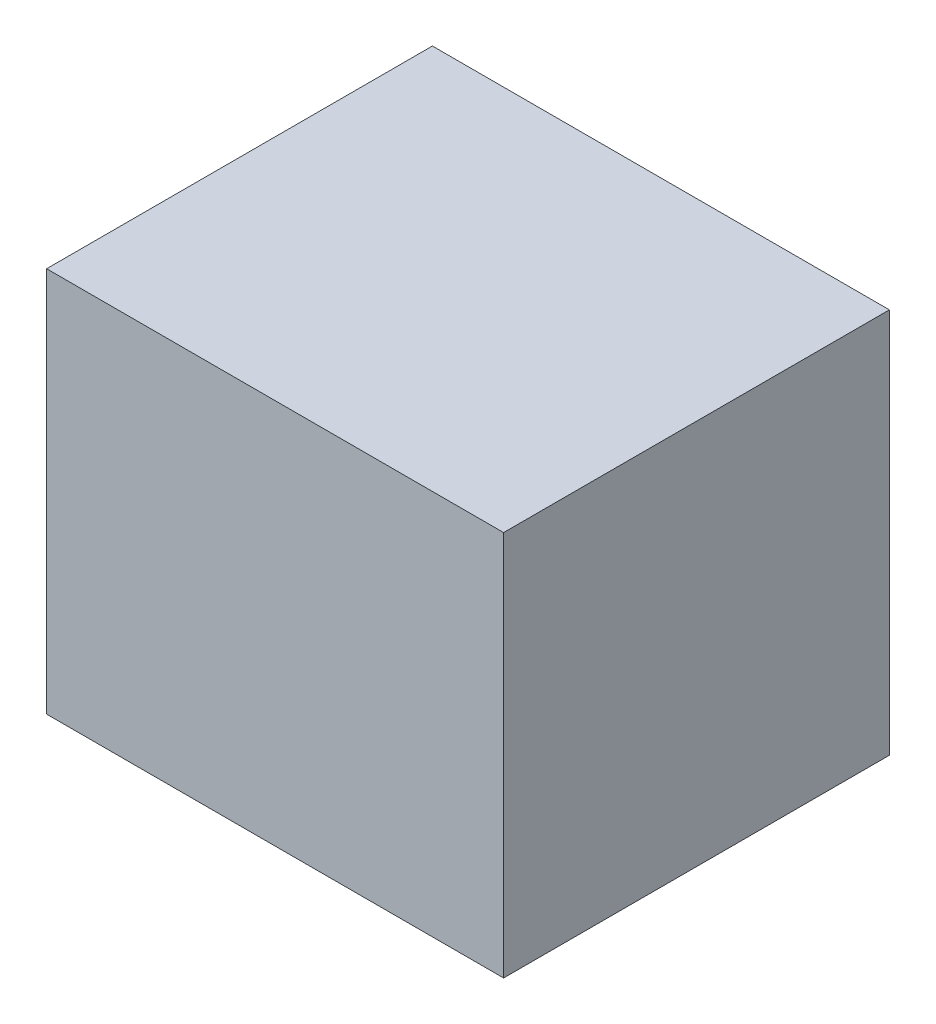
SolidWorks part; units mm, degrees
ref_plane "Front Plane" through (0, 0, 0) normal (0, 0, 1) x (1, 0, 0)
ref_plane "Top Plane" through (0, 0, 0) normal (0, 1, 0) x (1, 0, 0)
ref_plane "Right Plane" through (0, 0, 0) normal (1, 0, 0) x (0, 0, -1)
sketch "Sketch1" plane through (0, 0, 0) normal (0, 0, 1) x (1, 0, 0)
  line L1 (-122.2375, -103.1875) -> (122.2375, -103.1875)
  line L2 (-122.2375, -103.1875) -> (-122.2375, 103.1875)
  line L3 (-122.2375, 103.1875) -> (122.2375, 103.1875)
  line L4 (122.2375, -103.1875) -> (122.2375, 103.1875)
  line L5 (-122.2375, -103.1875) -> (122.2375, 103.1875) construction
  line L6 (-122.2375, 103.1875) -> (122.2375, -103.1875) construction
  point P0 (0, 0)
  dimension "D1" = 244.475
  dimension "D2" = 206.375
extrude "Boss-Extrude1" add sketch "Sketch1" against normal blind 206.375 contours L3 L4 L1 L2
shell "Shell1" thickness 3.175
sketch "Sketch2" plane through (0, 0, 0) normal (0, 0, 1) x (1, 0, 0)
  line L0 (-122.2375, -103.1875) -> (122.2375, -103.1875) construction
  line L1 (-66.3003, -100.1775) -> (51.5557, -100.1775)
  line L2 (-66.3003, -100.1775) -> (-66.3003, -59.2835)
  line L3 (-66.3003, -59.2835) -> (51.5557, -59.2835)
  line L4 (51.5557, -100.1775) -> (51.5557, -59.2835)
  line L5 (-119.0625, 68.2625) -> (-68.7705, 68.2625)
  line L6 (-119.0625, 68.2625) -> (-119.0625, -100.0125)
  line L7 (-119.0625, -100.0125) -> (-68.7705, -100.0125)
  line L8 (-68.7705, 68.2625) -> (-68.7705, -100.0125)
  line L9 (-122.2375, -103.1875) -> (-122.2375, 103.1875) construction
  line L10 (-66.3003, -46.8375) -> (51.5557, -46.8375)
  line L11 (55.093, -100.485) -> (95.987, -100.485)
  line L12 (55.093, -100.485) -> (55.093, 17.371)
  line L13 (55.093, 17.371) -> (95.987, 17.371)
  line L14 (95.987, -100.485) -> (95.987, 17.371)
  line L15 (99.3741, 18.9815) -> (124.7741, 18.9815)
  line L16 (99.3741, 18.9815) -> (99.3741, -100.3985)
  line L17 (99.3741, -100.3985) -> (124.7741, -100.3985)
  line L18 (124.7741, 18.9815) -> (124.7741, -100.3985)
  line L19 (-66.3003, -46.8375) -> (-66.3003, -5.9435)
  line L20 (-66.3003, -5.9435) -> (51.5557, -5.9435)
  line L21 (51.5557, -46.8375) -> (51.5557, -5.9435)
  line L22 (-66.3003, 6.5025) -> (51.5557, 6.5025)
  line L23 (-66.3003, 6.5025) -> (-66.3003, 47.3965)
  line L24 (-66.3003, 47.3965) -> (51.5557, 47.3965)
  line L25 (51.5557, 6.5025) -> (51.5557, 47.3965)
  line L26 (-66.3003, 59.8425) -> (51.5557, 59.8425)
  line L27 (-66.3003, 59.8425) -> (-66.3003, 100.7365)
  line L28 (-66.3003, 100.7365) -> (51.5557, 100.7365)
  line L29 (51.5557, 59.8425) -> (51.5557, 100.7365)
  dimension "D1" = 40.894
  dimension "D2" = 117.856
  dimension "D3" = 168.275
  dimension "D4" = 50.292
  dimension "D5" = 3.175
  dimension "D6" = 3.175
  dimension "D7" = 40.894
  dimension "D8" = 117.856
  dimension "D9" = 25.4
  dimension "D10" = 119.38
  dimension "D11" = 4
